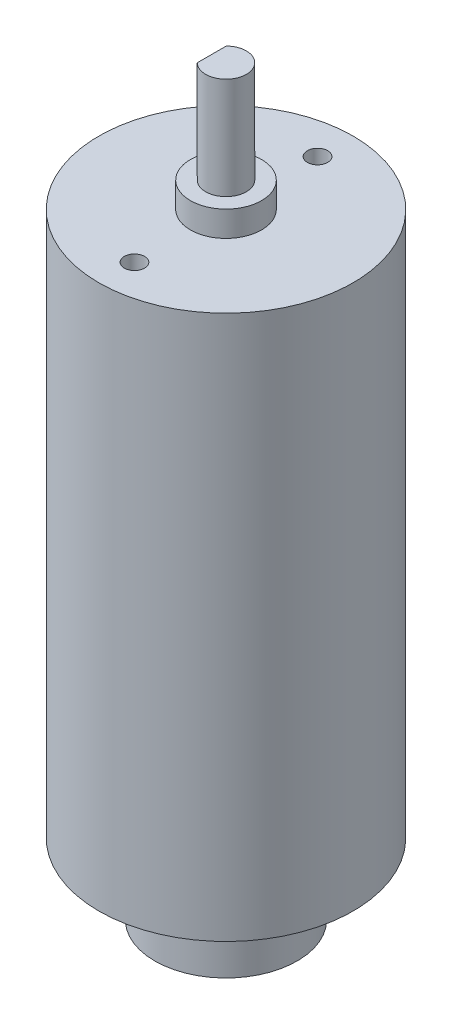
SolidWorks part; units mm, degrees
ref_plane "Front Plane" through (0, 0, 0) normal (0, 0, 1) x (1, 0, 0)
ref_plane "Top Plane" through (0, 0, 0) normal (0, 1, 0) x (1, 0, 0)
ref_plane "Right Plane" through (0, 0, 0) normal (1, 0, 0) x (0, 0, -1)
ref_plane "Plane1"
sketch "Sketch1" plane through (0, 0, 0) normal (0, 1, 0) x (-1, 0, 0)
  circle A0 centre (0, 0) radius 7
  dimension "D1" = 14
extrude "Extrusion1" add sketch "Sketch1" along normal blind 7
sketch "Sketch2" plane through (0, 7, 0) normal (0, 1, 0) x (-1, 0, 0)
  circle A0 centre (0, 0) radius 12.5
  dimension "D1" = 25
extrude "Extrusion2" add sketch "Sketch2" along normal blind 53.5
sketch "Sketch3" plane through (0, 60.5, 0) normal (0, 1, 0) x (-1, 0, 0)
  circle A0 centre (0, 0) radius 3.5
  dimension "D1" = 7
extrude "Extrusion3" add sketch "Sketch3" along normal blind 2.5
sketch "Sketch4" plane through (0, 63, 0) normal (0, 1, 0) x (-1, 0, 0)
  line L0 (1.4, 1.4283) -> (1.4, -1.4283)
  arc A0 (1.4, 1.4283) -> (1.4, -1.4283) centre (0, 0) ccw
  dimension "D1" = 4
extrude "Extrusion4" add sketch "Sketch4" along normal blind 10
ref_plane "Plane2"
sketch "Sketch5" plane through (0, 63, 0) normal (0, 1, 0) x (1, 0, 0)
  circle A0 centre (0, 0) radius 2
  dimension "D1" = 4
extrude "Extrusion5" add sketch "Sketch5" along normal blind 2
hole_wizard "Hole1" positions "Sketch7" profile "Sketch6" legacy
sketch "Sketch7" plane through (0, 60.5, 0) normal (0, 1, 0) x (1, 0, 0)
  point P1 (0, -9)
  point P2 (0, 9)
sketch "Sketch6" plane through (0, 60.5, 9) normal (1, 0, 0) x (0, 0, 1)
  line L0 (0, 0) -> (0, 10.6009)
  line L1 (0, 10.6009) -> (1, 10)
  line L2 (1, 10) -> (1, 0)
  line L4 (1, 0) -> (0, 0)
  line L6 (0, 10.6009) -> (-1, 10) construction
  line L7 (0, -4.2442) -> (0, 117.3081) construction
  dimension "Diameter" = 2
  dimension "Depth" = 10
  dimension "Drill Angle" = 118
